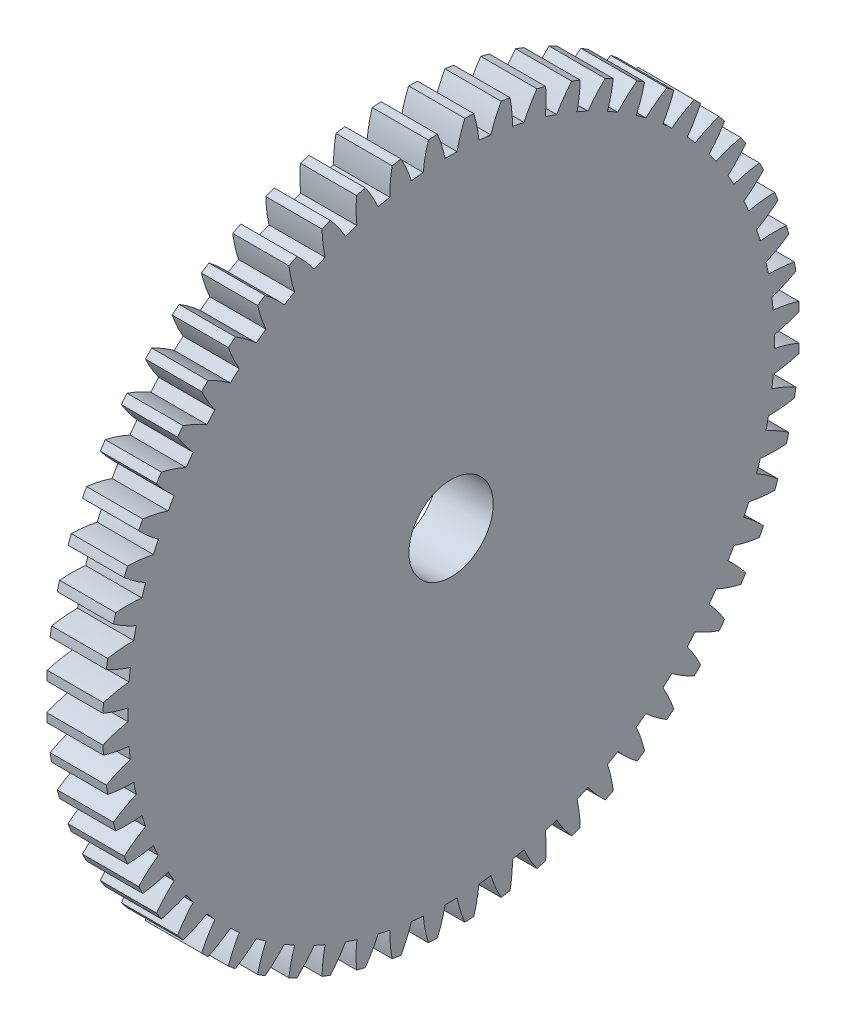
SolidWorks part; units mm, degrees
ref_plane "Plane1" through (0, 0, 0) normal (0, 0, 1) x (1, 0, 0)
ref_plane "Plane2" through (0, 0, 0) normal (0, 1, 0) x (1, 0, 0)
ref_plane "Plane3" through (0, 0, 0) normal (1, 0, 0) x (0, 0, -1)
sketch "HoldingSke" plane through (0, 0, 0) normal (0, 1, 0) x (1, 0, 0)
  line L0 (0, 0) -> (254, -439.9409)
  line L1 (-15, 0) -> (100, 0) construction
  line L2 (0, 0) -> (-2.1039, 2.3779)
  line L3 (0, 0) -> (-11.863, 4.5341)
  line L4 (0, 0) -> (4.318, 7.479)
  line L5 (0, 0) -> (-47.5972, -17.7524)
  line L6 (0, 0) -> (-5.2639, -3.5516)
  line L7 (-2.1039, 2.3779) -> (8.8308, 51.9871)
  line L8 (-76.2, 54.61) -> (-65.4837, 54.61)
  line L9 (-67.7845, 28.3722) -> (-49.3413, 33.142)
  line L10 (-76.2, 71.12) -> (104.1128, 71.12)
  line L11 (0, 0) -> (-6.35, 0)
  line L12 (-76.2, 101.6) -> (-76.1492, 101.6)
  line L13 (24.9733, 27.94) -> (52.9518, 28.4284)
  line L14 (24.9733, 27.94) -> (25.0241, 27.9398)
  line L15 (24.9733, 27.94) -> (100.4021, 29.52)
  circle A0 centre (0, 0) radius 4.7625
  circle A1 centre (0, 0) radius 36.5252
  circle A2 centre (0, 0) radius 38.1
  circle A3 centre (0, 0) radius 4.7625
  dimension "Hub_dia" = 76.2
  dimension "Bore" = 9.525
  dimension "MBD" = 9.525
  dimension "Pitch" = 508
  dimension "Overall_len" = 50.8
  dimension "Thickness" = 6.35
  dimension "OAL" = 50.8001
  dimension "T_dim" = 10.7163
  dimension "Ap" = 14.5
  dimension "H" = 19.05
  dimension "Pitch_radius" = 180.3128
  dimension "Width" = 6.35
  dimension "Backlash" = 0.0508
  dimension "Addendum_fac" = 1
  dimension "Dedendum_fac" = 1.2
  dimension "Clearance_fac" = 0.2
  dimension "Dedendum_add" = 0.0508
sketch "BasProSke" plane through (0, 0, 0) normal (0, 1, 0) x (1, 0, 0)
  line L0 (-10, 0) -> (60, 0) construction
  line L1 (0, 0) -> (0, 39.37)
  line L2 (0, 0) -> (6.35, 0)
  line L3 (6.35, 0) -> (6.35, 39.37)
  line L4 (6.35, 39.37) -> (0, 39.37)
  dimension "Thickness" = 6.35
revolve "Base-Revolve" add sketch "BasProSke" angle 360 about L0
sketch "TooCutSke" plane through (0, 0, 0) normal (1, 0, 0) x (0, 0, -1)
  line L1 (0, 0) -> (0, 107) construction
  line L2 (0, 0) -> (-1.0862, 38.0845) construction
  line L3 (0, 0) -> (-3.9869, 76.0739) construction
  line L4 (-1.0862, 38.0845) -> (-1.9934, 38.037) construction
  arc A0 (0.674, 36.519) -> (-0.674, 36.519) centre (0, 0) ccw
  arc A1 (1.5613, 39.3644) -> (-1.5613, 39.3644) centre (0, 0) ccw
  circle A2 centre (0, 0) radius 38.1 construction
  circle A3 centre (0, 0) radius 36.8864 construction
  arc A4 (-0.674, 36.519) -> (-1.5613, 39.3644) centre (-15.597, 33.4267) ccw
  arc A5 (1.5613, 39.3644) -> (0.674, 36.519) centre (15.597, 33.4267) ccw
  dimension "Half_CT" = 0.9084
extrude "ToothCut" cut sketch "TooCutSke" along normal through all
fillet "Breaks" [suppressed] radius 0.0254
fillet "RootFillets" [suppressed] radius 0.3048
pattern_circular "TeethCuts" count 60 every 6 about axis through (-10, 0, 0) along (1, 0, 0) of "ToothCut", "RootFillets", "Breaks"
sketch "HubNeaOneSke" plane through (0, 0, 0) normal (-1, 0, 0) x (0, 0, 1)
  circle A0 centre (0, 0) radius 36.5252
extrude "HubNearOne" [suppressed] add sketch "HubNeaOneSke" along normal blind 44.4501
sketch "HubNeaBotSke" plane through (0, 0, 0) normal (-1, 0, 0) x (0, 0, 1)
  circle A0 centre (0, 0) radius 36.5252
extrude "HubNearBoth" [suppressed] add sketch "HubNeaBotSke" along normal blind 22.225
ref_plane "FarPln" through (6.35, 0, 0) normal (1, 0, 0) x (0, 0, -1)
sketch "HubFarSke" plane through (6.35, 0, 0) normal (1, 0, 0) x (0, 0, -1)
  circle A0 centre (0, 0) radius 36.5252
extrude "HubFar" [suppressed] add sketch "HubFarSke" along normal blind 22.225
sketch "BorSke" plane through (0, 0, 0) normal (1, 0, 0) x (0, 0, -1)
  circle A0 centre (0, 0) radius 4.7625
  dimension "Diameter" = 9.525
extrude "Bore" cut sketch "BorSke" along normal mid plane 101.6001
sketch "KeySke" plane through (0, 0, 0) normal (1, 0, 0) x (0, 0, -1)
  line L0 (-1.1913, 0) -> (-1.1913, 5.9538)
  line L1 (-1.1913, 5.9538) -> (1.1913, 5.9538)
  line L2 (1.1913, 5.9538) -> (1.1913, 0)
  line L3 (0, 0) -> (0, 34) construction
  line L4 (-1.1913, 0) -> (1.1913, 0)
  dimension "Offset" = 5.9538
  dimension "Width" = 2.3825
extrude "Keyway" [suppressed] cut sketch "KeySke" along normal mid plane 101.6001
pattern_circular "Keyway2" [suppressed] count 2 every 90 about axis through (-10, 0, 0) along (1, 0, 0)
equation "' \"Pitch@HoldingSke\" = 4"
equation "' \"Num_teeth@HoldingSke\" = 12"
equation "' \"Ap@HoldingSke\" =  20"
equation "' \"Ap@HoldingSke\" = 20"
equation "' \"Width@HoldingSke\" = 0.5"
equation "' \"Hub_dia@HoldingSke\"= 1"
equation "' \"Hub_dia@HoldingSke\" = 1"
equation "' \"Overall_len@HoldingSke\" = 1.0"
equation "' \"Bore@HoldingSke\" = 0.75"
equation "' \"T_dim@HoldingSke\" = 0.85"
equation "' \"Width@KeySke\" = 0.25"
equation "' \"Show_teeth@HoldingSke\" = 13"
equation "' \"Backlash@HoldingSke\" = 0.009"
equation "' \"Addendum_fac@HoldingSke\" = 1.0"
equation "' \"Dedendum_fac@HoldingSke\" = 1.25"
equation "' \"Dedendum_add@HoldingSke\" = 0.00005"
equation "' \"Clearance_fac@HoldingSke\" = 0.25"
equation "' \"Pitch@HoldingSke\" = 0.5"
equation "' \"Num_teeth@HoldingSke\" = 23"
equation "' \"Show_teeth@HoldingSke\" = 23"
equation "' \"Backlash@HoldingSke\" = 0.0375"
equation "\"Overcut_dia@TooCutSke\" = (\"Num_teeth@HoldingSke\" + 2 * \"Addendum_fac@HoldingSke\") / \"Pitch@HoldingSke\" + 0.002"
equation "\"Pitch_dia@TooCutSke\" = \"Num_teeth@HoldingSke\" / \"Pitch@HoldingSke\""
equation "\"Base_dia@TooCutSke\" = \"Num_teeth@HoldingSke\" / \"Pitch@HoldingSke\" * cos((\"Ap@HoldingSke\"  * 3.14159265 / 180))"
equation "\"Root_dia@TooCutSke\" = (\"Num_teeth@HoldingSke\" + 2) / \"Pitch@HoldingSke\" - 2 * (\"Addendum_fac@HoldingSke\" + \"Dedendum_fac@HoldingSke\") / \"Pitch@HoldingSke\" - \"Dedendum_add@HoldingSke\" * 2"
equation "\"Half_ang@TooCutSke\" = 180 / \"Num_teeth@HoldingSke\""
equation "\"Half_CT@TooCutSke\" = \"Num_teeth@HoldingSke\" / \"Pitch@HoldingSke\" * sin((3.14159265 / 2 / \"Num_teeth@HoldingSke\")) / 2 - 7 * \"Backlash@HoldingSke\" / 4"
equation "\"Flank_rad@TooCutSke\" = \"Num_teeth@HoldingSke\" / \"Pitch@HoldingSke\" / 5"
equation "\"Radius@RootFillets\" = \"Clearance_fac@HoldingSke\" / \"Pitch@HoldingSke\" + \"Dedendum_add@HoldingSke\""
equation "\"Break_rad@Breaks\" = 0.02 / \"Pitch@HoldingSke\""
equation "\"Thickness@HoldingSke\" = \"Width@HoldingSke\""
equation "\"OAL@HoldingSke\" = \"Thickness@HoldingSke\""
equation "\"MHD@HoldingSke\" = (\"Num_teeth@HoldingSke\" + 2) / \"Pitch@HoldingSke\" - 2 * (\"Addendum_fac@HoldingSke\" + \"Dedendum_fac@HoldingSke\")  / \"Pitch@HoldingSke\" - \"Dedendum_add@HoldingSke\" * 2"
equation "\"MBD@HoldingSke\" = (\"Num_teeth@HoldingSke\" + 2) / \"Pitch@HoldingSke\" - 2 * (\"Addendum_fac@HoldingSke\" + \"Dedendum_fac@HoldingSke\")  / \"Pitch@HoldingSke\" - \"Dedendum_add@HoldingSke\" * 2 - 0.002"
equation "\"MHD@HoldingSke\" = ((sgn( \"MHD@HoldingSke\" - \"Hub_dia@HoldingSke\" )-1)*( \"MHD@HoldingSke\" - \"Hub_dia@HoldingSke\" ))/-2+ \"Hub_dia@HoldingSke\""
equation "\"MBD@HoldingSke\" = ((sgn( \"MBD@HoldingSke\" - \"Bore@HoldingSke\" )-1)*( \"MBD@HoldingSke\" - \"Bore@HoldingSke\" ))/-2+ \"Bore@HoldingSke\""
equation "\"OAL@HoldingSke\" = ((sgn( \"OAL@HoldingSke\" - \"Overall_len@HoldingSke\" )+1)*( \"OAL@HoldingSke\" - \"Overall_len@HoldingSke\" ))/2 + \"Overall_len@HoldingSke\" + 0.000002"
equation "\"Num_teeth@TeethCuts\" = int( \"Show_teeth@HoldingSke\" ) + 1"
equation "\"Num_teeth@TeethCuts\" = ((sgn( \"Num_teeth@TeethCuts\" - \"Num_teeth@HoldingSke\" )-1)*( \"Num_teeth@TeethCuts\" - \"Num_teeth@HoldingSke\" ))/-2+ \"Num_teeth@HoldingSke\""
equation "\"Num_teeth@TeethCuts\" = ((sgn( \"Num_teeth@TeethCuts\" - 2.0)+1)*( \"Num_teeth@TeethCuts\" - 2.0))/2 +2.0"
equation "\"Angle@TeethCuts\" = 360.0 / \"Num_teeth@HoldingSke\""
equation "\"Diameter@BasProSke\" = (\"Num_teeth@HoldingSke\" + 2 * \"Addendum_fac@HoldingSke\") / \"Pitch@HoldingSke\""
equation "\"Thickness@BasProSke\"  = \"Thickness@HoldingSke\""
equation "' \"Fillet_rad@BasProSke\" =  \"Thickness@HoldingSke\" * 0.05"
equation "' \"Fillet_rad@BasProSke\" = \"Thickness@HoldingSke\" * 0.05"
equation "\"MHD@HoldingSke\" = ((sgn( \"MHD@HoldingSke\" - \"Root_dia@TooCutSke\" )-1)*( \"MHD@HoldingSke\" - \"Root_dia@TooCutSke\" ))/-2+ \"Root_dia@TooCutSke\""
equation "\"Diameter@HubNeaOneSke\" = \"MHD@HoldingSke\""
equation "\"Length@HubNearOne\" = \"OAL@HoldingSke\" - \"Thickness@BasProSke\""
equation "\"Diameter@HubNeaBotSke\" = \"MHD@HoldingSke\""
equation "\"Length@HubNearBoth\" = ( \"OAL@HoldingSke\" - \"Thickness@BasProSke\" ) / 2.0"
equation "\"Thickness@FarPln\" = \"Thickness@BasProSke\""
equation "\"Diameter@HubFarSke\" = \"MHD@HoldingSke\""
equation "\"Length@HubFar\" = ( \"OAL@HoldingSke\" - \"Thickness@BasProSke\" ) / 2.0"
equation "\"Diameter@BorSke\" = \"MBD@HoldingSke\""
equation "\"D1@Bore\" = \"OAL@HoldingSke\" * 2.0"
equation "\"D1@Keyway\" = \"OAL@HoldingSke\" * 2.0"
equation "\"Offset@KeySke\" = \"T_dim@HoldingSke\" - \"MBD@HoldingSke\" / 2.0"
